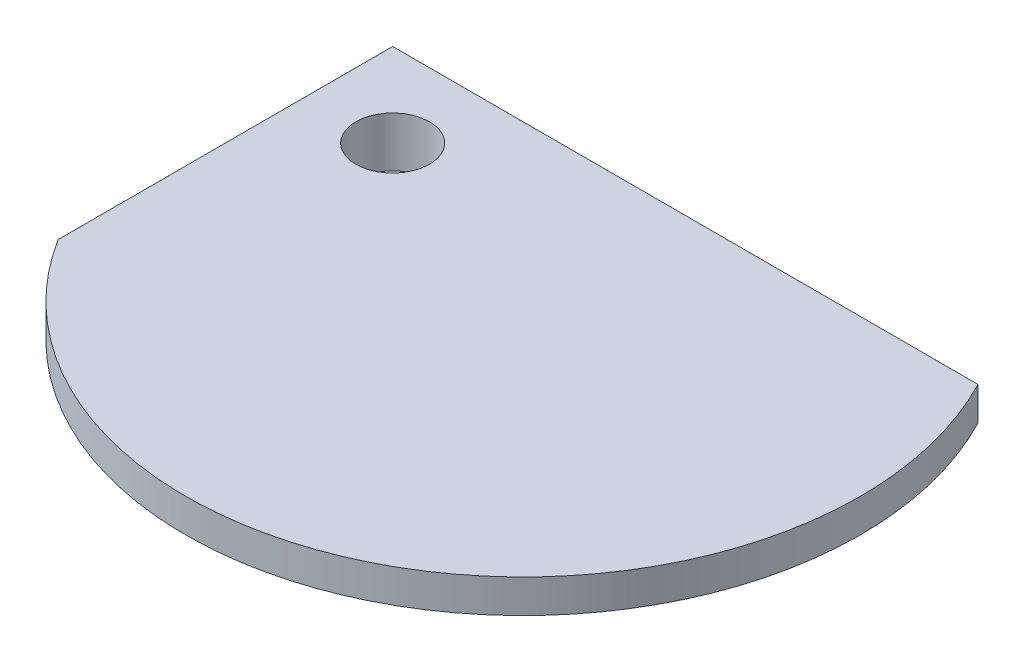
SolidWorks part; units mm, degrees
ref_plane "Front Plane" through (0, 0, 0) normal (0, 0, 1) x (1, 0, 0)
ref_plane "Top Plane" through (0, 0, 0) normal (0, 1, 0) x (1, 0, 0)
ref_plane "Right Plane" through (0, 0, 0) normal (1, 0, 0) x (0, 0, -1)
sketch "Sketch1" plane through (0, 0, 0) normal (0, 1, 0) x (1, 0, 0)
  circle A0 centre (0, 0) radius 2.794
  circle A1 centre (0, 0) radius 4.572
  dimension "D1" = 5.588
  dimension "D2" = 1.778
extrude "Boss-Extrude1" add sketch "Sketch1" along normal blind 3.2004
sketch "Sketch2" plane through (0, 3.2004, 0) normal (0, 1, 0) x (1, 0, 0)
  circle A0 centre (0, 0) radius 1.397
  circle A1 centre (0, 0) radius 4.572
  dimension "D1" = 2.794
extrude "Boss-Extrude2" add sketch "Sketch2" along normal blind 1.778
sketch "Sketch3" plane through (0, 4.9784, 0) normal (0, 1, 0) x (1, 0, 0)
  circle A0 centre (0, 0) radius 2.794
  circle A1 centre (0, 0) radius 6.35
  dimension "D1" = 12.7
  dimension "D2" = 5.588
extrude "Boss-Extrude3" add sketch "Sketch3" along normal blind 1.27 separate body
sketch "Sketch4" plane through (0, 6.2484, 0) normal (0, 1, 0) x (1, 0, 0)
  line L1 (-6.35, 6.35) -> (38.1, 6.35)
  line L2 (-6.35, 6.35) -> (-6.35, -19.05)
  circle A0 centre (0, 0) radius 2.794
  circle A1 centre (0, 0) radius 6.35 construction
  arc A5 (38.1, 6.35) -> (-6.35, -19.05) centre (15.3759, -5.4765) cw
  dimension "D1" = 44.45
  dimension "D2" = 25.4
extrude "Boss-Extrude4" add sketch "Sketch4" along normal blind 2.54
